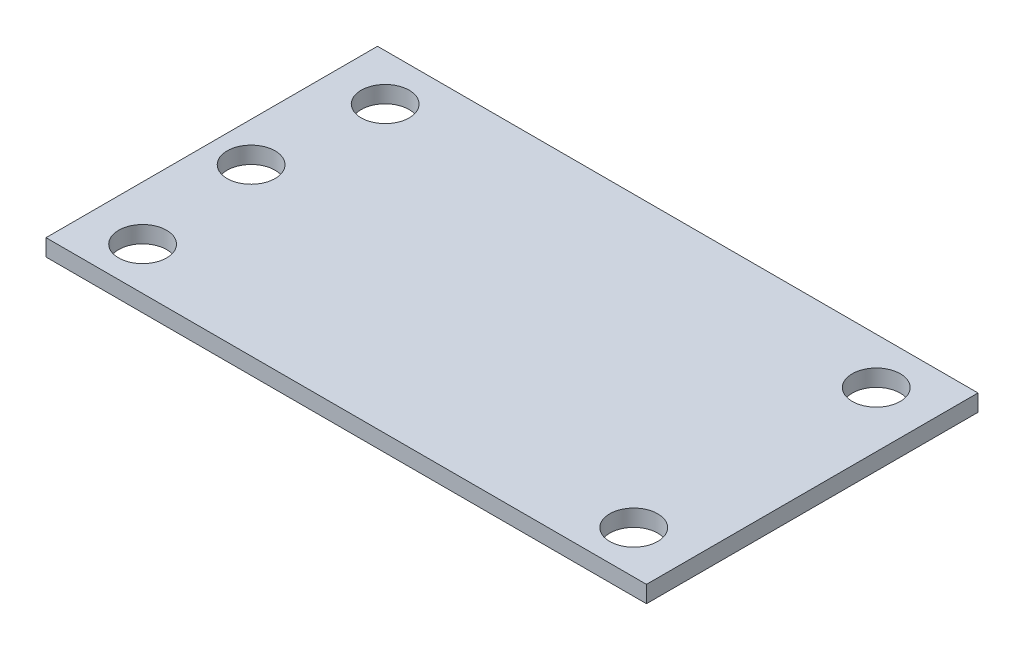
SolidWorks part; units mm, degrees
ref_plane "Front Plane" through (0, 0, 0) normal (0, 0, 1) x (1, 0, 0)
ref_plane "Top Plane" through (0, 0, 0) normal (0, 1, 0) x (1, 0, 0)
ref_plane "Right Plane" through (0, 0, 0) normal (1, 0, 0) x (0, 0, -1)
sketch "Sketch4" plane through (0, 0, 0) normal (0, 1, 0) x (1, 0, 0)
  line L1 (125.1317, 69.0847) -> (-125.1317, 69.0847)
  line L2 (125.1317, 69.0847) -> (125.1317, -69.0847)
  line L3 (125.1317, -69.0847) -> (-125.1317, -69.0847)
  line L4 (-125.1317, 69.0847) -> (-125.1317, -69.0847)
  line L5 (125.1317, 69.0847) -> (-125.1317, -69.0847) construction
  line L6 (125.1317, -69.0847) -> (-125.1317, 69.0847) construction
  point P0 (0, 0)
extrude "Boss-Extrude1" add sketch "Sketch4" along normal blind 7
sketch "Sketch5" plane through (0, 0, 0) normal (0, 1, 0) x (1, 0, 0)
  circle A0 centre (-102.6853, 49.826) radius 10
  circle A1 centre (101.994, 49.826) radius 10
  circle A2 centre (101.994, -51.2636) radius 10
  circle A3 centre (-102.6853, -51.2636) radius 10
  point P8 (0, 0)
  point P9 (0, 0)
  point P10 (0, 0)
  point P11 (0, 0)
  dimension "D1" = 20
  dimension "D2" = 20
  dimension "D3" = 20
  dimension "D4" = 20
extrude "Cut-Extrude1" cut sketch "Sketch5" against normal through all and the other way blind 60
sketch "Sketch9" plane through (0, 0, 0) normal (0, 1, 0) x (1, 0, 0)
  circle A0 centre (-108.7268, 0) radius 10
  point P2 (0, 0)
  dimension "D1" = 20
extrude "Cut-Extrude6" cut sketch "Sketch9" against normal blind 76 and the other way blind 68
